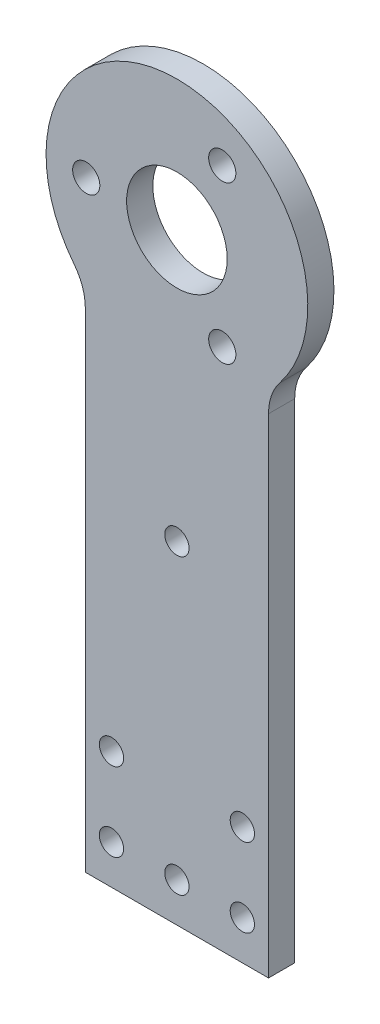
SolidWorks part; units mm, degrees
material "6061-T6 (SS)"
ref_plane "Front Plane" through (0, 0, 0) normal (0, 0, 1) x (1, 0, 0)
ref_plane "Top Plane" through (0, 0, 0) normal (0, 1, 0) x (1, 0, 0)
ref_plane "Right Plane" through (0, 0, 0) normal (1, 0, 0) x (0, 0, -1)
sketch "Sketch1" plane through (0, 0, 0) normal (0, 0, 1) x (1, 0, 0)
  line L0 (-11.1125, -11.337) -> (-11.1125, -73.025)
  line L1 (11.1125, -11.337) -> (11.1125, -73.025)
  line L2 (11.1125, -73.025) -> (-11.1125, -73.025)
  line L3 (0, 0) -> (0, -73.025) construction
  arc A0 (11.1125, -11.337) -> (-11.1125, -11.337) centre (0, 0) ccw
  circle A1 centre (-11, 0) radius 1.65
  circle A2 centre (5.5, 9.5263) radius 1.65
  circle A3 centre (5.5, -9.5263) radius 1.65
  circle A4 centre (0, 0) radius 6.1
  point P15 (0, 0)
  dimension "D1" = 22.225
  dimension "D4" = 15.875
  dimension "D5" = 3.3
  dimension "D7" = 12.2
  dimension "D2" = 73.025
  dimension "D3" = 11
  dimension "D6" = 3
extrude "Boss-Extrude1" add sketch "Sketch1" along normal blind 3.175
hole_wizard "#4 Clearance Hole2" positions "Sketch2" profile "Sketch3" hole size "#4" standard "ANSI Inch"
sketch "Sketch2" plane through (0, 0, 0) normal (0, 0, -1) x (-1, 0, 0)
  line L0 (0, -73.025) -> (0, -65.4664) construction
  line L1 (11.1125, -73.025) -> (-11.1125, -73.025) construction
  point P0 (7.9375, -68.2625)
  point P2 (-7.9375, -68.2625)
  point P4 (-7.9375, -58.7375)
  point P6 (7.9375, -58.7375)
  dimension "D1" = 15.875
  dimension "D2" = 9.525
  dimension "D3" = 4.7625
sketch "Sketch3" plane through (-7.9375, -68.2625, 0) normal (1, 0, 0) x (0, 1, 0)
  line L0 (0, 0) -> (0, 10.7912)
  line L1 (0, 10.7912) -> (1.4732, 9.906)
  line L2 (1.4732, 9.906) -> (1.4732, 0)
  line L5 (1.4732, 0) -> (0, 0)
  line L10 (0, 10.7912) -> (-1.4732, 9.906) construction
  line L11 (0, -6.35) -> (0, 107.95) construction
  dimension "Hole Dia." = 2.9464
  dimension "Hole Depth" = 9.906
  dimension "Drill Angle" = 118
sketch "Sketch4" plane through (0, 0, 0) normal (0, 0, -1) x (-1, 0, 0)
  line L0 (0, -73.025) -> (0, -47.1239) construction
  line L1 (11.1125, -73.025) -> (-11.1125, -73.025) construction
  line L3 (-2.5, -68.525) -> (2.5, -68.525)
  line L4 (-2.5, -68.525) -> (-2.5, -53.525)
  line L5 (-2.5, -53.525) -> (2.5, -53.525)
  line L6 (2.5, -68.525) -> (2.5, -53.525)
  line L7 (-2.5, -68.525) -> (2.5, -53.525) construction
  line L8 (-2.5, -53.525) -> (2.5, -68.525) construction
  point P5 (0, -61.025)
  dimension "D1" = 15
  dimension "D2" = 5
  dimension "D3" = 12
extrude "SERVO-SLOT" [suppressed] cut sketch "Sketch4" against normal up to next
fillet "TOOLING-RADIUS" [suppressed] radius 1.5875
hole_wizard "#4 Clearance Hole1" positions "Sketch5" profile "Sketch6" hole size "#4" standard "ANSI Inch" end condition up to next
sketch "Sketch5" plane through (0, 0, 0) normal (0, 0, -1) x (-1, 0, 0)
  line L0 (11.1125, -73.025) -> (-11.1125, -73.025) construction
  point P0 (0, -68.2625)
  point P2 (0, -32.7025)
  dimension "D1" = 35.56
  dimension "D2" = 4.7625
sketch "Sketch6" plane through (0, -68.2625, 0) normal (1, 0, 0) x (0, 1, 0)
  line L0 (0, 0) -> (0, 3.175)
  line L1 (0, 3.175) -> (1.4732, 3.175)
  line L2 (1.4732, 3.175) -> (1.4732, 0)
  line L5 (1.4732, 0) -> (0, 0)
  line L11 (0, -6.35) -> (0, 107.95) construction
  dimension "Thru Hole Dia." = 2.9464
  dimension "Thru Hole Depth" = 3.175
fillet "Fillet1" radius 6.35 2 edges at (-11.1125, -11.337, 1.5875) (11.1125, -11.337, 1.5875)
